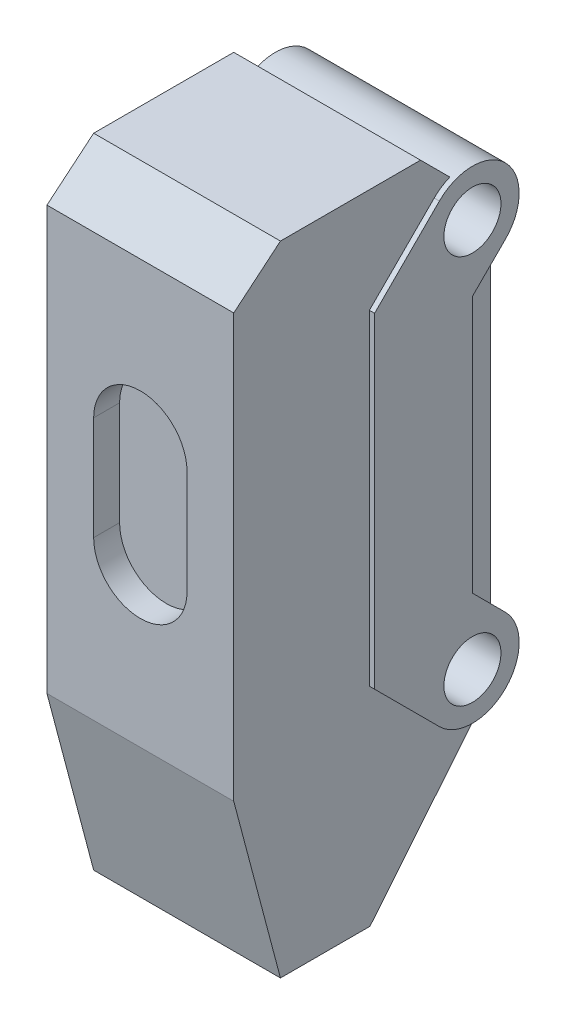
SolidWorks part; units mm, degrees
ref_plane "정면" through (0, 0, 0) normal (0, 0, 1) x (1, 0, 0)
ref_plane "윗면" through (0, 0, 0) normal (0, 1, 0) x (1, 0, 0)
ref_plane "우측면" through (0, 0, 0) normal (1, 0, 0) x (0, 0, -1)
sketch "스케치1" plane through (0, 0, 0) normal (0, 0, 1) x (1, 0, 0)
  line L1 (-3.6, 12.3) -> (3.6, 12.3)
  line L2 (-3.6, 12.3) -> (-3.6, -12.3)
  line L3 (-3.6, -12.3) -> (3.6, -12.3)
  line L4 (3.6, 12.3) -> (3.6, -12.3)
  line L5 (-3.6, 12.3) -> (3.6, -12.3) construction
  line L6 (-3.6, -12.3) -> (3.6, 12.3) construction
  point P0 (0, 0)
  dimension "D1" = 24.6
  dimension "D2" = 7.2
extrude "보스-돌출1" add sketch "스케치1" along normal blind 10.8
sketch "스케치5" plane through (-3.6, 0, 0) normal (-1, 0, 0) x (0, 0, 1)
  line L0 (0, 12.3) -> (0, 8.7)
  line L1 (0, 8.7) -> (3.6, 12.3)
  line L2 (10.8, 12.3) -> (0, 12.3) construction
  line L3 (3.6, 12.3) -> (0, 12.3)
  dimension "D1" = 3.6
  dimension "D2" = 3.6
extrude "컷-돌출3" cut sketch "스케치5" against normal up to surface (7.2 mm away) up to face at (3.6, 0, 5.4)
sketch "스케치2" plane through (3.6, 0, 0) normal (1, 0, 0) x (0, 0, -1)
  line L0 (-10.8, -5.5) -> (-9, -12.3)
  line L1 (-10.8, -12.3) -> (-10.8, 12.3) construction
  line L2 (-10.8, -12.3) -> (0, -12.3) construction
  line L3 (-9, -12.3) -> (-10.8, -12.3)
  line L4 (-10.8, -12.3) -> (-10.8, -5.5)
  line L5 (-10.8, 12.3) -> (-10.8, 10.8)
  line L6 (-10.8, 10.8) -> (-9, 12.3)
  line L7 (-10.8, 12.3) -> (-3.6, 12.3) construction
  line L8 (-9, 12.3) -> (-10.8, 12.3)
  line L10 (-0.9, 7.8544) -> (-0.1295, 8.8295)
  line L11 (-0.9, 7.8544) -> (-0.9, -3.8544)
  line L15 (-0.1295, 8.8295) -> (0, 8.7)
  line L16 (-5.55, -12.3) -> (0, -12.3)
  line L21 (-5.55, -12.3) -> (0, -5.5)
  line L22 (0, -5.5) -> (0, -12.3)
  line L26 (-0.9, -3.8544) -> (-0.1295, -5.3943)
  line L27 (-0.1295, -5.3943) -> (0, -5.3943)
  line L28 (0, -12.3) -> (0, 8.7) construction
  line L29 (0, -5.3943) -> (0, 8.7)
  point P16 (0, 0)
  point P24 (0, 0)
  point P26 (0, 0)
  point P27 (0, 0)
  point P29 (0, 0)
  point P30 (0, 0)
  dimension "D2" = 6.8
  dimension "D4" = 6.8
  dimension "D5" = 1.5
  dimension "D6" = 1.8
  dimension "D7" = 1.8
  dimension "D11" = 5.55
extrude "컷-돌출1" cut sketch "스케치2" against normal blind 10.8
sketch "스케치3" plane through (3.6, 0, 0) normal (1, 0, 0) x (0, 0, -1)
  line L1 (-9, -12.3) -> (-5.55, -12.3) construction
  line L2 (-3.0728, 10.7728) -> (-5.5711, 8.2745)
  line L3 (-5.5711, 8.2745) -> (-5.5711, -4.2745)
  line L4 (-5.5711, -4.2745) -> (-3.0728, -6.7728)
  line L5 (-0.5272, -4.2272) -> (-1.8, -2.9544)
  line L6 (-1.8, -2.9544) -> (-1.8, 6.9544)
  line L7 (-1.8, 6.9544) -> (-0.5272, 8.2272)
  line L8 (-10.8, -5.5) -> (-10.8, 10.8) construction
  circle A0 centre (-1.8, 9.5) radius 1.1
  circle A1 centre (-1.8, -5.5) radius 1.1
  arc A2 (-3.0728, -6.7728) -> (-0.5272, -4.2272) centre (-1.8, -5.5) ccw
  arc A3 (-0.5272, 8.2272) -> (-3.0728, 10.7728) centre (-1.8, 9.5) ccw
  point P10 (0, 0)
  point P15 (-1.8, 2)
  point P16 (-5.5711, 2)
  dimension "D3" = 2.2
  dimension "D4" = 2.2
  dimension "D11" = 1.8
  dimension "D13" = 1.8
  dimension "D1" = 15
  dimension "D2" = 6.8
  dimension "D5" = 135
  dimension "D6" = 135
  dimension "D7" = 135
  dimension "D8" = 135
  dimension "D9" = 0
  dimension "D10" = 0
  dimension "D12" = 9
extrude "보스-돌출3" add sketch "스케치3" along normal blind 0.2 and the other way blind 3.6
ref_plane "평면1" through (0, 0, 0) normal (-1, 0, 0) x (0, 0, 1)
sketch "스케치4" plane through (-3.6, 0, 0) normal (-1, 0, 0) x (0, 0, 1)
  circle A0 centre (1.8, 9.5) radius 1.1
  circle A1 centre (1.8, -5.5) radius 1.1
  point P6 (0, 0)
  point P7 (0, 0)
  dimension "D1" = 2.2
extrude "컷-돌출2" cut sketch "스케치4" against normal through all both and the other way through all
mirror "대칭 복사2" about plane through (0, 0, 0) normal (-1, 0, 0) of "보스-돌출3"
sketch "스케치6" plane through (0, 0, 10.8) normal (0, 0, 1) x (1, 0, 0)
  line L0 (0, 4.6) -> (0, 0.6) construction
  line L1 (0, 5.1484) -> (0, -5.1484) construction
  line L2 (1.8, 4.6) -> (1.8, 0.6)
  line L3 (-1.8, 4.6) -> (-1.8, 0.6)
  line L4 (-3.6, -12.3) -> (3.6, -12.3) construction
  arc A0 (1.8, 4.6) -> (-1.8, 4.6) centre (0, 4.6) ccw
  arc A1 (-1.8, 0.6) -> (1.8, 0.6) centre (0, 0.6) ccw
  point P5 (0, 2.6)
  dimension "D2" = 1.8
  dimension "D1" = 4
  dimension "D3" = 14.9
extrude "컷-돌출4" cut sketch "스케치6" against normal blind 1
